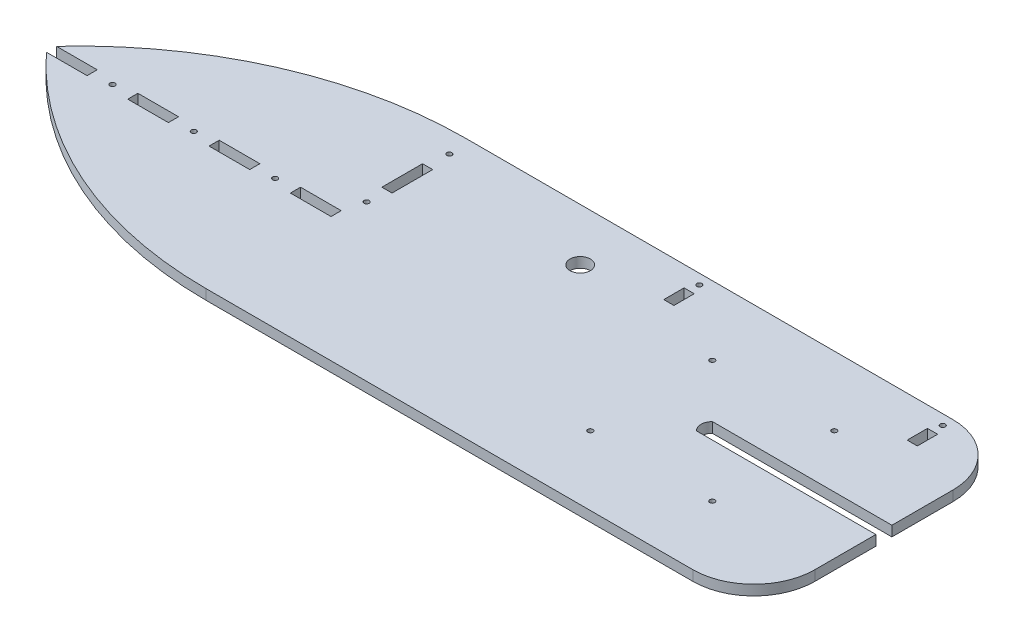
SolidWorks part; units mm, degrees
material "6061 Alloy"
ref_plane "Front Plane" through (0, 0, 0) normal (0, 0, 1) x (1, 0, 0)
ref_plane "Top Plane" through (0, 0, 0) normal (0, 1, 0) x (1, 0, 0)
ref_plane "Right Plane" through (0, 0, 0) normal (1, 0, 0) x (0, 0, -1)
sketch "Sketch1" plane through (0, 0, 0) normal (0, 1, 0) x (1, 0, 0)
  line L0 (140.2981, -30.2407) -> (241.8981, -30.2407)
  line L1 (140.2981, -40.2483) -> (241.8981, -40.2483)
  line L2 (241.8981, -40.2483) -> (241.8981, -78.3483)
  line L3 (140.2981, -30.2407) -> (129.8086, -30.2407)
  line L4 (140.2981, -40.2483) -> (129.8086, -40.2483)
  line L5 (241.8981, -30.2407) -> (241.8981, 7.8593)
  line L6 (203.7981, 45.9593) -> (-100.2463, 45.9593)
  line L7 (203.7981, -116.4483) -> (-100.2463, -116.4483)
  line L8 (-100.2463, -32.0695) -> (-100.2463, -38.4195)
  line L9 (-100.2463, -38.4195) -> (-125.6463, -38.4195)
  line L10 (-125.6463, -38.4195) -> (-125.6463, -32.0695)
  line L11 (-125.6463, -32.0695) -> (-100.2463, -32.0695)
  line L12 (-151.0463, -32.0695) -> (-176.4463, -32.0695)
  line L13 (-176.4463, -32.0695) -> (-176.4463, -38.4195)
  line L14 (-151.0463, -32.0695) -> (-151.0463, -38.4195)
  line L15 (-151.0463, -38.4195) -> (-176.4463, -38.4195)
  line L16 (-227.2463, -32.0695) -> (-201.8463, -32.0695)
  line L17 (-201.8463, -32.0695) -> (-201.8463, -38.4195)
  line L18 (-201.8463, -38.4195) -> (-227.2463, -38.4195)
  line L19 (-227.2463, -38.4195) -> (-227.2463, -32.0695)
  line L20 (-278.0463, -32.0695) -> (-252.6463, -32.0695)
  line L21 (-252.6463, -32.0695) -> (-252.6463, -38.4195)
  line L22 (-252.6463, -38.4195) -> (-278.0463, -38.4195)
  line L23 (-93.8963, -6.6695) -> (-100.2463, -6.6695)
  line L24 (-93.8963, -6.6695) -> (-93.8963, 18.7305)
  line L25 (-93.8963, 18.7305) -> (-100.2463, 18.7305)
  line L26 (-100.2463, 18.7305) -> (-100.2463, -6.6695)
  line L27 (203.7981, 33.2593) -> (206.9731, 33.2593)
  line L28 (206.9731, 33.2593) -> (206.9731, 20.5593)
  line L29 (206.9731, 20.5593) -> (200.6231, 20.5593)
  line L30 (200.6231, 20.5593) -> (200.6231, 33.2593)
  line L31 (200.6231, 33.2593) -> (203.7981, 33.2593)
  line L32 (51.7759, 33.2593) -> (54.9509, 33.2593)
  line L33 (54.9509, 33.2593) -> (54.9509, 20.5593)
  line L34 (54.9509, 20.5593) -> (48.6009, 20.5593)
  line L35 (48.6009, 20.5593) -> (48.6009, 33.2593)
  line L36 (48.6009, 33.2593) -> (51.7759, 33.2593)
  arc A0 (203.7981, -116.4483) -> (241.8981, -78.3483) centre (203.7981, -78.3483) ccw
  arc A1 (241.8981, 7.8593) -> (203.7981, 45.9593) centre (203.7981, 7.8593) ccw
  circle A2 centre (172.8037, -73.3445) radius 1.5875
  circle A3 centre (96.6037, -73.3445) radius 1.5875
  circle A4 centre (96.6037, 2.8555) radius 1.5875
  circle A5 centre (172.8037, 2.8555) radius 1.5875
  circle A6 centre (-138.3463, -35.2445) radius 1.5875
  circle A7 centre (-189.1463, -35.2445) radius 1.5875
  circle A8 centre (-239.9463, -35.2445) radius 1.5875
  arc A9 (-100.2463, 45.9593) -> (-278.0463, -32.0695) centre (-100.2463, -195.6267) ccw
  arc A10 (-278.0463, -38.4195) -> (-100.2463, -116.4483) centre (-100.2463, 125.1377) ccw
  circle A11 centre (-97.0713, -19.3695) radius 1.5875
  circle A12 centre (-97.0713, 32.3449) radius 1.5875
  circle A13 centre (3.6923, 13.254) radius 6.35
  circle A14 centre (203.7981, 39.6093) radius 1.5875
  circle A15 centre (51.7759, 39.6093) radius 1.5875
  arc A16 (129.8086, -30.2407) -> (129.8086, -40.2483) centre (134.7037, -35.2445) ccw
extrude "Boss-Extrude1" add sketch "Sketch1" along normal blind 6.35
